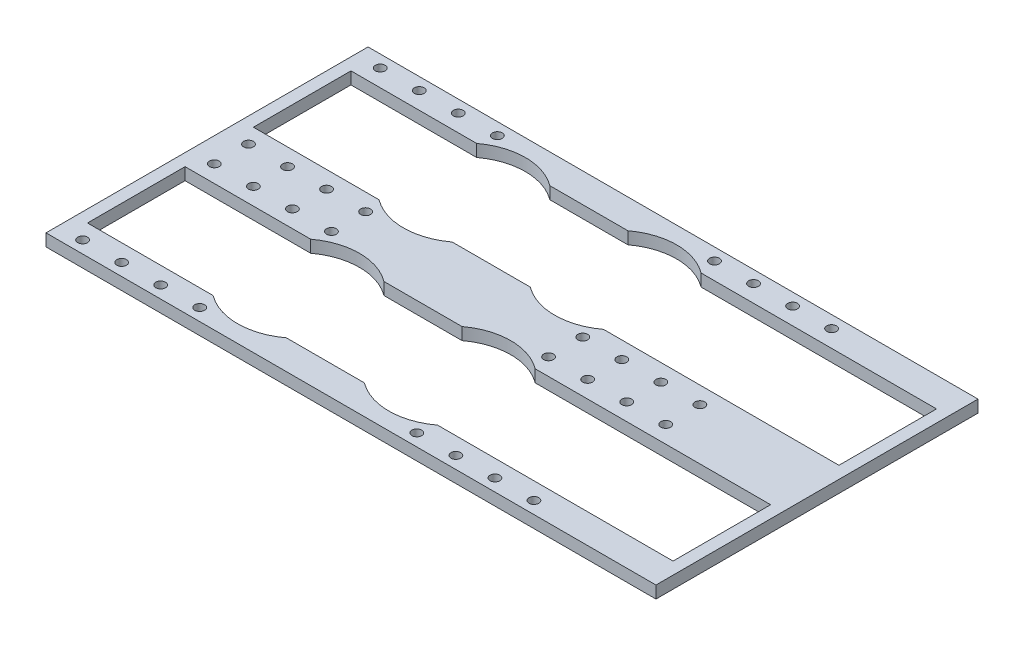
SolidWorks part; units mm, degrees
ref_plane "Front Plane" through (0, 0, 0) normal (0, 0, 1) x (1, 0, 0)
ref_plane "Top Plane" through (0, 0, 0) normal (0, 1, 0) x (1, 0, 0)
ref_plane "Right Plane" through (0, 0, 0) normal (1, 0, 0) x (0, 0, -1)
sketch "Sketch1" plane through (0, 0, 0) normal (0, 1, 0) x (1, 0, 0)
  line L1 (-80, 33) -> (80, 33)
  line L2 (-80, 33) -> (-80, -33)
  line L3 (-80, -33) -> (80, -33)
  line L4 (80, 33) -> (80, -33)
  line L5 (-80, 33) -> (80, -33) construction
  line L6 (-80, -33) -> (80, 33) construction
  point P0 (0, 0)
  dimension "D1" = 160
  dimension "D2" = 66
extrude "Boss-Extrude1" add sketch "Sketch1" along normal blind 40
sketch "Sketch2" plane through (0, 0, 33) normal (0, 0, 1) x (1, 0, 0)
  line L0 (80, 40) -> (80, 0) construction
  line L1 (-80, 40) -> (80, 40) construction
  line L2 (-80, 40) -> (50, 40)
  line L3 (-80, 40) -> (-80, 2.5)
  line L4 (-80, 2.5) -> (50, 2.5)
  line L5 (50, 40) -> (50, 2.5)
  line L6 (-80, 40) -> (50, 2.5) construction
  line L7 (-80, 2.5) -> (50, 40) construction
  line L8 (-80, 40) -> (-80, 0) construction
  circle A0 centre (70, 20) radius 4
  point P4 (80, 20)
  point P5 (-15, 21.25)
  dimension "D1" = 8
  dimension "D2" = 10
  dimension "D3" = 37.5
  dimension "D4" = 130
extrude "Cut-Extrude1" cut sketch "Sketch2" against normal through all
sketch "Sketch3" plane through (0, 40, 0) normal (0, 1, 0) x (1, 0, 0)
  line L0 (-80, 33) -> (-80, -33) construction
  line L1 (80, 33) -> (50, 33) construction
  line L2 (-75, 30.5) -> (-67, 30.5) construction
  line L3 (-75, 3.5) -> (-67, 3.5) construction
  line L4 (0, 0) -> (13.7346, 0) construction
  line L5 (-80, 33) -> (-80, -33) construction
  line L6 (-6.5, 30.5) -> (1.5, 30.5) construction
  line L7 (-75, 30.5) -> (-75, 3.5) construction
  line L8 (-77.5, 27) -> (42.5, 27)
  line L9 (-77.5, 27) -> (-77.5, 7)
  line L10 (-77.5, 7) -> (42.5, 7)
  line L11 (42.5, 27) -> (42.5, 7)
  line L12 (-6.5, 3.5) -> (1.5, 3.5) construction
  line L13 (-6.5, -3.5) -> (1.5, -3.5) construction
  line L14 (-75, -30.5) -> (-75, -3.5) construction
  line L15 (-6.5, -30.5) -> (1.5, -30.5) construction
  line L16 (-75, -3.5) -> (-67, -3.5) construction
  line L17 (-75, -30.5) -> (-67, -30.5) construction
  line L18 (42.5, -27) -> (42.5, -7)
  line L19 (-77.5, -7) -> (42.5, -7)
  line L20 (-77.5, -27) -> (-77.5, -7)
  line L21 (-77.5, -27) -> (42.5, -27)
  circle A0 centre (-75, 30.5) radius 1
  circle A1 centre (-75, 3.5) radius 1
  circle A2 centre (-67, 30.5) radius 1
  circle A3 centre (-59, 30.5) radius 1
  circle A4 centre (-51, 30.5) radius 1
  circle A11 centre (-67, 3.5) radius 1
  circle A12 centre (-59, 3.5) radius 1
  circle A13 centre (-51, 3.5) radius 1
  circle A50 centre (-6.5, 30.5) radius 1
  circle A51 centre (-6.5, 3.5) radius 1
  circle A52 centre (1.5, 30.5) radius 1
  circle A53 centre (9.5, 30.5) radius 1
  circle A54 centre (17.5, 30.5) radius 1
  circle A55 centre (1.5, 3.5) radius 1
  circle A56 centre (9.5, 3.5) radius 1
  circle A57 centre (17.5, 3.5) radius 1
  circle A58 centre (17.5, -3.5) radius 1
  circle A59 centre (9.5, -3.5) radius 1
  circle A60 centre (1.5, -3.5) radius 1
  circle A61 centre (17.5, -30.5) radius 1
  circle A62 centre (9.5, -30.5) radius 1
  circle A63 centre (1.5, -30.5) radius 1
  circle A64 centre (-6.5, -3.5) radius 1
  circle A65 centre (-6.5, -30.5) radius 1
  circle A66 centre (-51, -3.5) radius 1
  circle A67 centre (-59, -3.5) radius 1
  circle A68 centre (-67, -3.5) radius 1
  circle A69 centre (-51, -30.5) radius 1
  circle A70 centre (-59, -30.5) radius 1
  circle A71 centre (-67, -30.5) radius 1
  circle A72 centre (-75, -3.5) radius 1
  circle A73 centre (-75, -30.5) radius 1
  point P96 (-77.5, 17)
  point P97 (-75, 17)
  dimension "D1" = 2
  dimension "D3" = 2.5
  dimension "D4" = 27
  dimension "D12" = 2
  dimension "D2" = 5
  dimension "D6" = 8
  dimension "D8" = 8
  dimension "D9" = 20
  dimension "D10" = 120
  dimension "D11" = 2.5
  dimension "D13" = 44.5
  dimension "D15" = 8
  dimension "D17" = 8
  dimension "D5" = 4
  dimension "D7" = 4
  dimension "D14" = 4
  dimension "D16" = 4
extrude "Cut-Extrude2" cut sketch "Sketch3" against normal through all
sketch "Sketch4" plane through (0, 2.5, 0) normal (0, 1, 0) x (1, 0, 0)
  line L1 (-77.5, -7) -> (42.5, -7) construction
  line L2 (-77.5, 27) -> (42.5, 27) construction
  circle A0 centre (-44.25, -17) radius 12.5
  circle A1 centre (-51, -3.5) radius 1 construction
  circle A2 centre (-44.25, 17) radius 12.5
  circle A3 centre (-13.25, 17) radius 12.5
  circle A4 centre (-13.25, -17) radius 12.5
  circle A5 centre (-6.5, -3.5) radius 1 construction
  dimension "D1" = 25
  dimension "D4" = 6.75
  dimension "D2" = 6.75
  dimension "D3" = 10
  dimension "D5" = 10
extrude "Cut-Extrude3" cut sketch "Sketch4" against normal through all
sketch "Sketch5" plane through (0, 40, 0) normal (0, 1, 0) x (1, 0, 0)
  line L0 (42.5, -7) -> (42.5, -27) construction
  line L1 (45, 33) -> (80, 33)
  line L2 (45, 33) -> (45, -33)
  line L3 (45, -33) -> (80, -33)
  line L4 (80, 33) -> (80, -33)
  line L5 (45, 33) -> (80, -33) construction
  line L6 (45, -33) -> (80, 33) construction
  line L7 (-80, 33) -> (50, 33) construction
  point P0 (62.5, 0)
  dimension "D1" = 2.5
extrude "Cut-Extrude4" cut sketch "Sketch5" against normal through all
